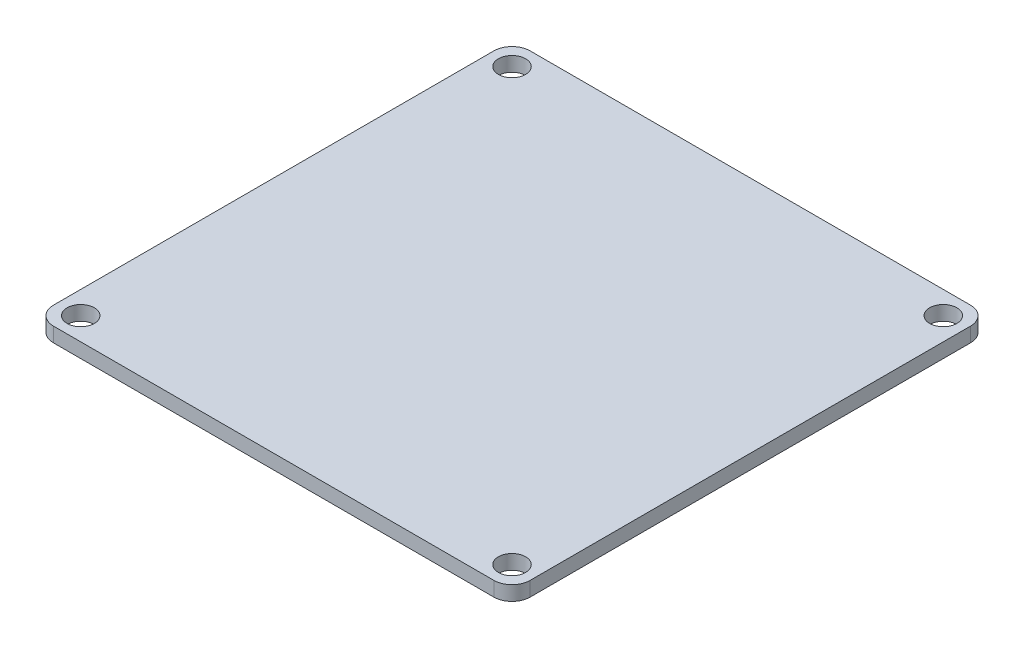
SolidWorks part; units mm, degrees
ref_plane "前视基准面" through (0, 0, 0) normal (0, 0, 1) x (1, 0, 0)
ref_plane "上视基准面" through (0, 0, 0) normal (0, 1, 0) x (1, 0, 0)
ref_plane "右视基准面" through (0, 0, 0) normal (1, 0, 0) x (0, 0, -1)
sketch "Sketch1" plane through (0, 0, 0) normal (0, 1, 0) x (1, 0, 0)
  line L0 (-26.25, 26.25) -> (-26.25, -26.25)
  line L1 (-23.75, 23.75) -> (23.75, 23.75) construction
  line L2 (-23.75, 23.75) -> (-23.75, -23.75) construction
  line L3 (-23.75, -23.75) -> (23.75, -23.75) construction
  line L4 (23.75, 23.75) -> (23.75, -23.75) construction
  line L5 (-23.75, 23.75) -> (23.75, -23.75) construction
  line L6 (-23.75, -23.75) -> (23.75, 23.75) construction
  line L7 (-26.25, -26.25) -> (26.25, -26.25)
  line L8 (26.25, 26.25) -> (26.25, -26.25)
  line L9 (-26.25, 26.25) -> (26.25, 26.25)
  line L10 (0, 0) -> (0, 7.4212) construction
  line L11 (0, 0) -> (6.2589, 0) construction
  circle A0 centre (-23.75, 23.75) radius 1.5
  circle A1 centre (23.75, 23.75) radius 1.5
  circle A2 centre (23.75, -23.75) radius 1.5
  circle A3 centre (-23.75, -23.75) radius 1.5
  point P0 (0, 0)
  dimension "D3" = 3
  dimension "D1" = 47.5
  dimension "D2" = 2.5
extrude "Boss-Extrude1" add sketch "Sketch1" along normal blind 1.6
fillet "Fillet1" radius 2 4 edges at (-26.25, 0.8, -26.25) (-26.25, 0.8, 26.25) (26.25, 0.8, -26.25) (26.25, 0.8, 26.25)
